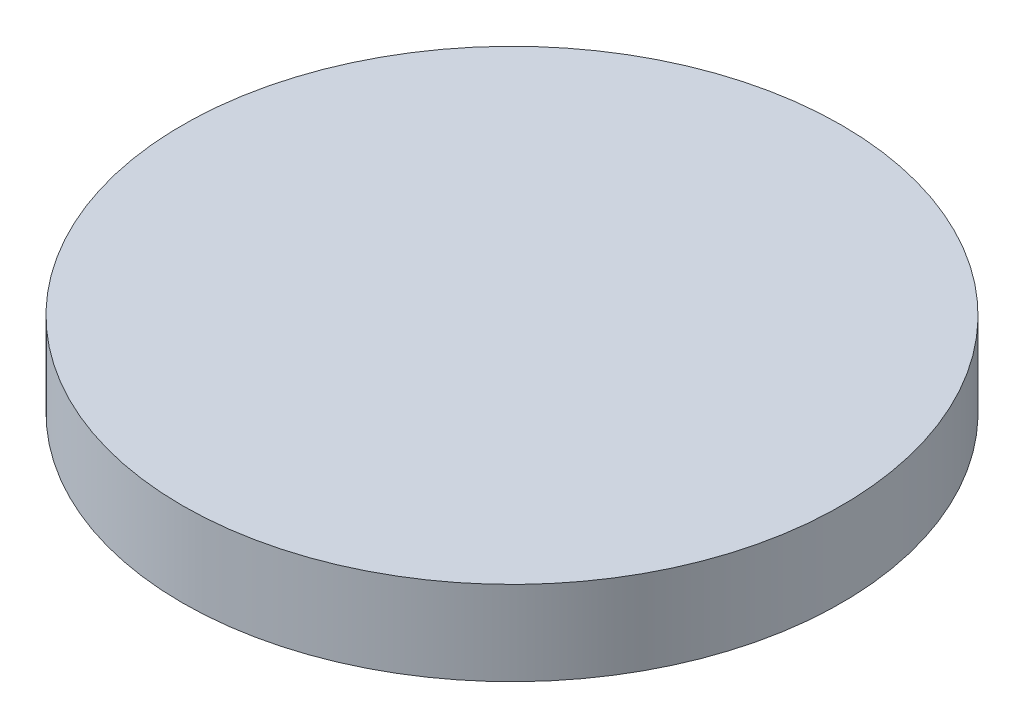
SolidWorks part; units mm, degrees
ref_plane "Front Plane" through (0, 0, 0) normal (0, 0, 1) x (1, 0, 0)
ref_plane "Top Plane" through (0, 0, 0) normal (0, 1, 0) x (1, 0, 0)
ref_plane "Right Plane" through (0, 0, 0) normal (1, 0, 0) x (0, 0, -1)
sketch "Sketch1" plane through (0, 0, 0) normal (0, 1, 0) x (1, 0, 0)
  circle A0 centre (0, 0) radius 18.375
  dimension "D1" = 36.75
extrude "Boss-Extrude1" add sketch "Sketch1" along normal blind 4.698
